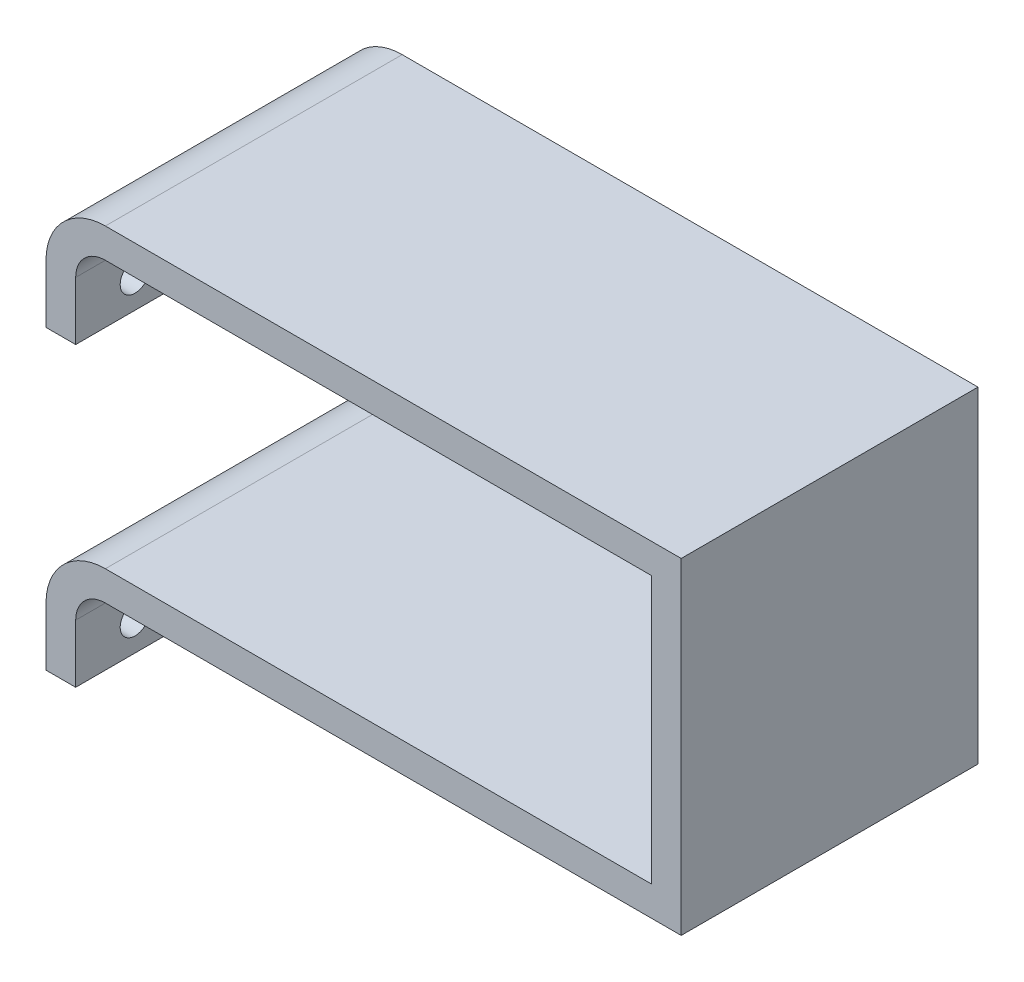
SolidWorks part; units mm, degrees
ref_plane "Front Plane" through (0, 0, 0) normal (0, 0, 1) x (1, 0, 0)
ref_plane "Top Plane" through (0, 0, 0) normal (0, 1, 0) x (1, 0, 0)
ref_plane "Right Plane" through (0, 0, 0) normal (1, 0, 0) x (0, 0, -1)
sketch "Sketch1" plane through (0, 0, 0) normal (0, 0, 1) x (1, 0, 0)
  line L0 (0, 0) -> (0, 19.6)
  line L3 (0, 19.6) -> (20, 19.6) construction
  line L4 (20, 19.6) -> (20, 39.6) construction
  line L5 (0, 0) -> (10, 0)
  line L6 (20, 29.6) -> (214, 29.6)
  line L9 (0, 0) -> (10, 0)
  line L10 (20, 39.6) -> (204, 39.6)
  line L11 (214, 29.6) -> (214, 139.6)
  line L12 (10, 19.6) -> (10, 0)
  line L13 (204, 39.6) -> (204, 129.6)
  line L14 (0, 0) -> (0, 19.6)
  line L15 (214, 139.6) -> (20, 139.6)
  line L16 (204, 129.6) -> (20, 129.6)
  line L17 (0, 100) -> (0, 119.6)
  line L18 (20, 39.6) -> (20, 160.1437) construction
  line L19 (0, 100) -> (10, 100)
  line L20 (10, 119.6) -> (10, 100)
  arc A2 (20, 39.6) -> (0, 19.6) centre (20, 19.6) ccw
  arc A4 (20, 29.6) -> (10, 19.6) centre (20, 19.6) ccw
  arc A5 (20, 139.6) -> (0, 119.6) centre (20, 119.6) ccw
  arc A6 (20, 129.6) -> (10, 119.6) centre (20, 119.6) ccw
  point P15 (265, 39.6)
  point P19 (265, 29.6)
  dimension "D5" = 184
  dimension "D1" = 19.6
  dimension "D2" = 20
  dimension "D3" = 110
  dimension "D4" = 194
  dimension "D6" = 90
extrude "Boss-Extrude2" add sketch "Sketch1" along normal blind 100
sketch "Sketch2" plane through (0, 0, 0) normal (-1, 0, 0) x (0, 0, 1)
  line L0 (100, 0) -> (0, 0) construction
  line L1 (0, 0) -> (0, 19.6) construction
  line L2 (50, 0) -> (50, 42.8019) construction
  circle A0 centre (20, 10) radius 5
  circle A1 centre (80, 10) radius 5
  dimension "D1" = 10
  dimension "D2" = 10
  dimension "D3" = 20
extrude "Cut-Extrude1" cut sketch "Sketch2" against normal through all
sketch "Sketch3" plane through (0, 0, 0) normal (-1, 0, 0) x (0, 0, 1)
  line L0 (20, 105) -> (20, 110) construction
  line L6 (100, 100) -> (0, 100) construction
  circle A1 centre (20, 110) radius 5
  circle A2 centre (80, 110) radius 5
  dimension "D1" = 10
  dimension "D2" = 10
extrude "Cut-Extrude2" cut sketch "Sketch3" against normal blind 10
